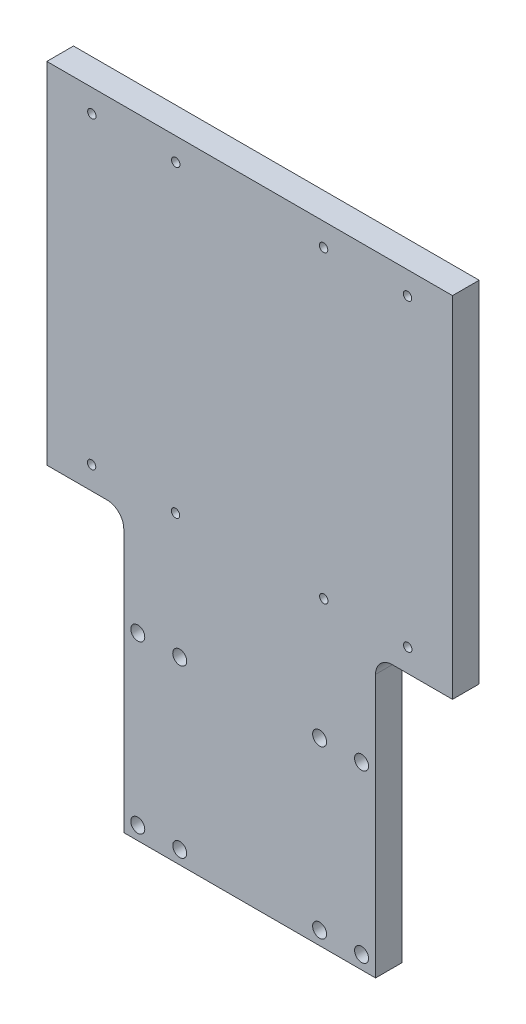
SolidWorks part; units mm, degrees
ref_plane "Plano frontal" through (0, 0, 0) normal (0, 0, 1) x (1, 0, 0)
ref_plane "Plano superior" through (0, 0, 0) normal (0, 1, 0) x (1, 0, 0)
ref_plane "Plano direito" through (0, 0, 0) normal (1, 0, 0) x (0, 0, -1)
sketch "Esboço1" plane through (0, 0, 0) normal (0, 0, 1) x (1, 0, 0)
  line L0 (71.505, 62.5) -> (-71.505, -62.5) construction
  line L1 (-71.505, 62.5) -> (71.505, 62.5)
  line L2 (-71.505, 62.5) -> (-71.505, -62.5)
  line L3 (-71.505, -62.5) -> (-45, -62.5)
  line L4 (71.505, 62.5) -> (71.505, -62.5)
  line L5 (0, 0) -> (0, -38.7566) construction
  line L7 (-45, -62.5) -> (-45, -162.5)
  line L8 (-45, -162.5) -> (45, -162.5)
  line L9 (45, -62.5) -> (45, -162.5)
  line L10 (45, -62.5) -> (71.505, -62.5)
  dimension "D1" = 143.01
  dimension "D2" = 125
  dimension "D3" = 45
  dimension "D4" = 45
  dimension "D5" = 100
extrude "Ressalto-extrusão1" add sketch "Esboço1" along normal blind 9.53
sketch "Esboço2" plane through (0, 0, 9.53) normal (0, 0, 1) x (1, 0, 0)
  line L0 (-45, -98.2) -> (45, -98.2) construction
  line L1 (0, -98.2) -> (0, -157.7) construction
  line L2 (0, -127.95) -> (17.3469, -127.95) construction
  line L3 (-45, -157.7) -> (45, -157.7) construction
  line L4 (-45, -62.5) -> (-45, -162.5) construction
  line L5 (45, -162.5) -> (45, -62.5) construction
  line L6 (-45, -162.5) -> (45, -162.5) construction
  line L7 (0, -157.7) -> (0, -159.6013) construction
  circle A0 centre (-40, -157.7) radius 2.5
  circle A1 centre (-25, -157.7) radius 2.5
  circle A2 centre (25, -157.7) radius 2.5
  circle A3 centre (40, -157.7) radius 2.5
  circle A4 centre (40, -98.2) radius 2.5
  circle A5 centre (25, -98.2) radius 2.5
  circle A6 centre (-25, -98.2) radius 2.5
  circle A7 centre (-40, -98.2) radius 2.5
  dimension "D1" = 59.5
  dimension "D5" = 4.8
  dimension "D6" = 5
  dimension "D7" = 5
  dimension "D8" = 5
  dimension "D9" = 20
extrude "Corte-extrusão1" cut sketch "Esboço2" against normal up to next
sketch "Esboço3" plane through (0, 0, 0) normal (0, 0, -1) x (-1, 0, 0)
  circle A0 centre (56.505, -54.325) radius 1.5
  circle A1 centre (26.505, -54.325) radius 1.5
  circle A2 centre (-26.505, -54.325) radius 1.5
  circle A3 centre (-56.505, -54.325) radius 1.5
  circle A4 centre (-56.4232, 54.325) radius 1.5
  circle A5 centre (-26.4232, 54.325) radius 1.5
  circle A6 centre (56.4232, 54.325) radius 1.5
  circle A7 centre (26.4232, 54.325) radius 1.5
extrude "Corte-extrusão2" cut sketch "Esboço3" against normal up to next
sketch "Croquis1" plane through (0, 0, 9.53) normal (0, 0, 1) x (1, 0, 0)
  line L1 (-71.505, 62.5) -> (-72.505, 62.5)
  line L2 (-71.505, 62.5) -> (-71.505, -62.5)
  line L3 (-71.505, -62.5) -> (-72.505, -62.5)
  line L4 (-72.505, 62.5) -> (-72.505, -62.5)
  line L5 (71.505, -62.5) -> (72.505, -62.5)
  line L6 (71.505, -62.5) -> (71.505, 62.5)
  line L7 (71.505, 62.5) -> (72.505, 62.5)
  line L8 (72.505, -62.5) -> (72.505, 62.5)
  dimension "D1" = 1
  dimension "D2" = 1
extrude "Saliente-Extruir1" add sketch "Croquis1" against normal up to surface (9.53 mm away) up to face at (-27.9232, 54.325, 0)
fillet "Redondeo1" radius 6 2 edges at (45, -62.5, 4.765) (-45, -62.5, 4.765)
